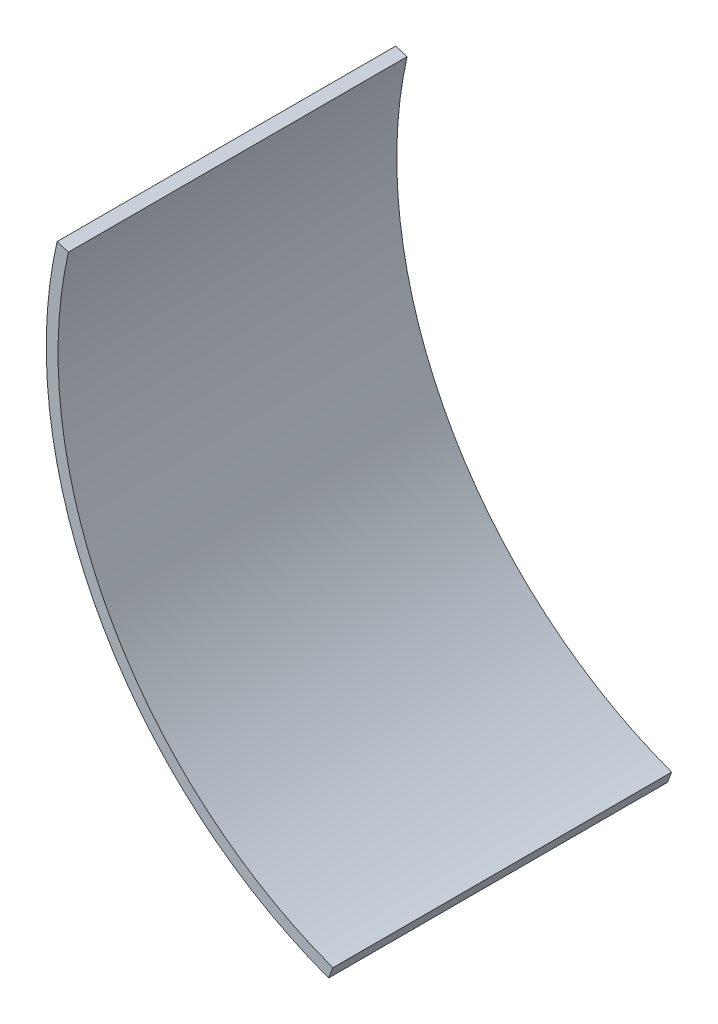
SolidWorks part; units mm, degrees
material "AISI 1020"
ref_plane "Ön Düzlem" through (0, 0, 0) normal (0, 0, 1) x (1, 0, 0)
ref_plane "Üst Düzlem" through (0, 0, 0) normal (0, 1, 0) x (1, 0, 0)
ref_plane "Sağ Düzlem" through (0, 0, 0) normal (1, 0, 0) x (0, 0, -1)
sketch "Model" plane through (0, 0, 0) normal (0, 0, 1) x (1, 0, 0)
  line L0 (3052.5593, 1293.1262) -> (3057.9972, 1307.108)
  line L1 (2707.2752, 1930.5821) -> (2722.1639, 1925.8852)
  arc A0 (2707.81, 1930.4134) -> (3052.5593, 1293.1262) centre (3243.4508, 1808.2837) ccw
  arc A1 (2722.1639, 1925.8852) -> (3057.9972, 1307.108) centre (3243.4508, 1808.2837) ccw
extrude "Yükseklik-Ekstrüzyon1" add sketch "Model" along normal blind 430 contours A1 L1 A0 L0
